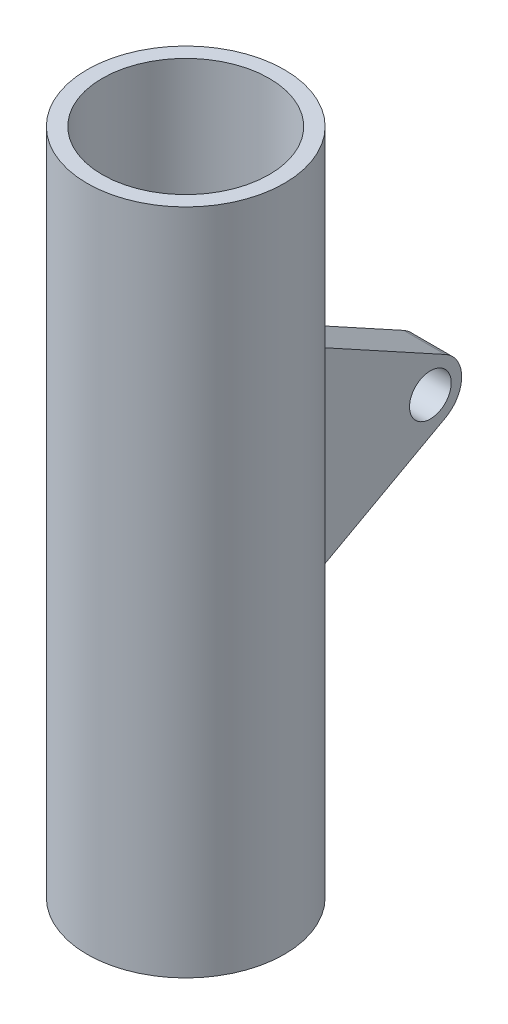
SolidWorks part; units mm, degrees
ref_plane "Front Plane" through (0, 0, 0) normal (0, 0, 1) x (1, 0, 0)
ref_plane "Top Plane" through (0, 0, 0) normal (0, 1, 0) x (1, 0, 0)
ref_plane "Right Plane" through (0, 0, 0) normal (1, 0, 0) x (0, 0, -1)
sketch "Sketch1" plane through (0, 0, 0) normal (0, 1, 0) x (1, 0, 0)
  circle A0 centre (0, 0) radius 25.4
  circle A1 centre (0, 0) radius 30
  dimension "D1" = 50.8
  dimension "D2" = 60
extrude "Boss-Extrude1" add sketch "Sketch1" along normal blind 203.2
ref_plane "Plane1" through (0, 0, -30) normal (0, 0, -1) x (-1, 0, 0)
sketch "Sketch2" plane through (0, 0, -30) normal (0, 0, -1) x (-1, 0, 0)
  line L0 (-6.35, 69.85) -> (-6.35, 133.35)
  line L1 (-6.35, 69.85) -> (6.35, 69.85)
  line L2 (-6.35, 133.35) -> (6.35, 133.35)
  line L3 (6.35, 69.85) -> (6.35, 133.35)
  line L4 (-6.35, 69.85) -> (6.35, 133.35) construction
  line L5 (-6.35, 133.35) -> (6.35, 69.85) construction
  line L6 (0, 203.2) -> (0, 0) construction
  line L7 (25.4, 203.2) -> (-25.4, 203.2) construction
  line L8 (30, 203.2) -> (30, 0)
  line L9 (30, 203.2) -> (30, 0) construction
  line L10 (30, 0) -> (-30, 0)
  line L11 (30, 0) -> (-30, 0) construction
  line L12 (-30, 0) -> (-30, 203.2)
  line L13 (-30, 0) -> (-30, 203.2) construction
  line L14 (-30, 203.2) -> (30, 203.2)
  line L15 (-30, 203.2) -> (30, 203.2) construction
  point P1 (0, 101.6)
  point P14 (0, 138.4974)
  point P15 (0, 0)
  point P16 (0, 172.1771)
  point P17 (0, 101.6)
  dimension "D1" = 63.5
  dimension "D2" = 12.7
extrude "Boss-Extrude2" add sketch "Sketch2" along normal blind 50.8 and the other way up to next
sketch "Sketch3" plane through (6.35, 0, 0) normal (1, 0, 0) x (0, 0, -1)
  line L0 (-30, 0) -> (-30, 203.2)
  line L1 (-30, 0) -> (-30, 203.2) construction
  line L2 (-30, 203.2) -> (30, 203.2)
  line L3 (-30, 203.2) -> (30, 203.2) construction
  line L4 (30, 203.2) -> (30, 133.35)
  line L5 (30, 203.2) -> (30, 133.35) construction
  line L6 (30, 133.35) -> (80.8, 133.35)
  line L7 (30, 133.35) -> (80.8, 133.35) construction
  line L8 (80.8, 133.35) -> (80.8, 69.85)
  line L9 (80.8, 133.35) -> (80.8, 69.85) construction
  line L10 (80.8, 69.85) -> (30, 69.85)
  line L11 (80.8, 69.85) -> (30, 69.85) construction
  line L12 (30, 69.85) -> (30, 0)
  line L13 (30, 69.85) -> (30, 0) construction
  line L14 (30, 0) -> (-30, 0)
  line L15 (30, 0) -> (-30, 0) construction
  line L16 (30, 133.35) -> (72.6789, 109.9522)
  line L17 (30, 69.85) -> (72.6789, 93.2478)
  line L18 (30, 133.35) -> (30, 69.85)
  circle A0 centre (68.1, 101.6) radius 6.35
  circle A1 centre (68.1, 101.6) radius 9.525
  point P8 (30, 69.85)
  point P11 (71.1464, 92.5753)
  point P12 (80.8, 101.6)
  line M10 (80.8, 133.35) -> (29.3203, 133.35)
  line M12 (29.3203, 69.85) -> (80.8, 69.85)
  line M13 (80.8, 69.85) -> (80.8, 133.35)
  dimension "D2" = 12.7
  dimension "D3" = 19.05
  dimension "D1" = 12.7
extrude "Cut-Extrude3" cut sketch "Sketch3" against normal up to next and the other way through all contours A1 L17 L16 M12 M13 M10 | A0
